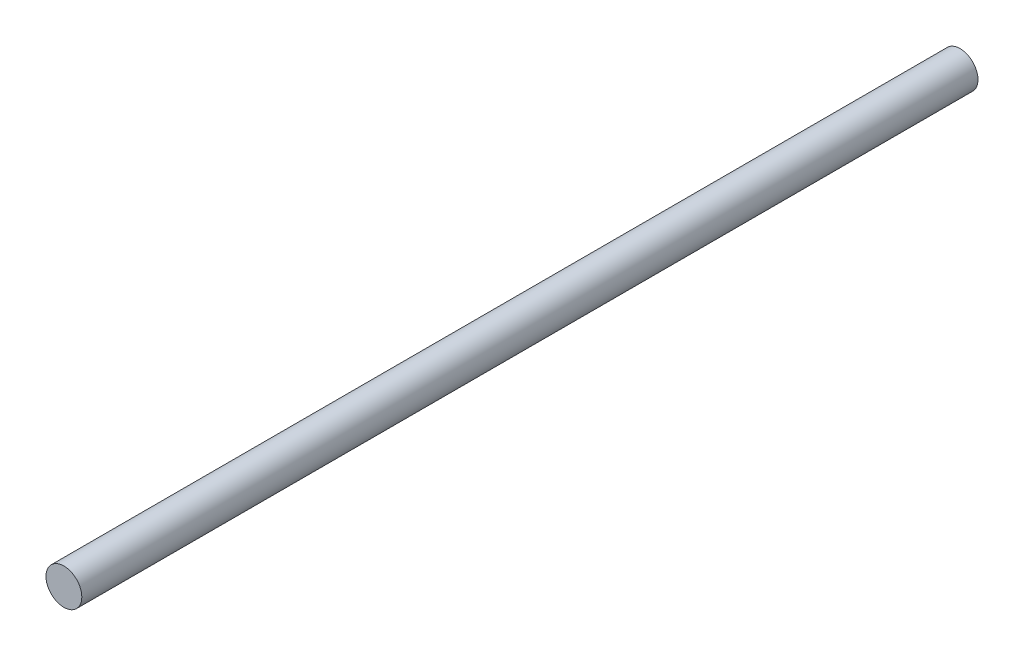
SolidWorks part; units mm, degrees
ref_plane "Plan de face" through (0, 0, 0) normal (0, 0, 1) x (1, 0, 0)
ref_plane "Plan de dessus" through (0, 0, 0) normal (0, 1, 0) x (1, 0, 0)
ref_plane "Plan de droite" through (0, 0, 0) normal (1, 0, 0) x (0, 0, -1)
sketch "Esquisse1" plane through (0, 0, 0) normal (0, 0, 1) x (1, 0, 0)
  circle A0 centre (0, 0) radius 3
  dimension "D1" = 6
extrude "Boss.-Extru.1" add sketch "Esquisse1" along normal blind 150
